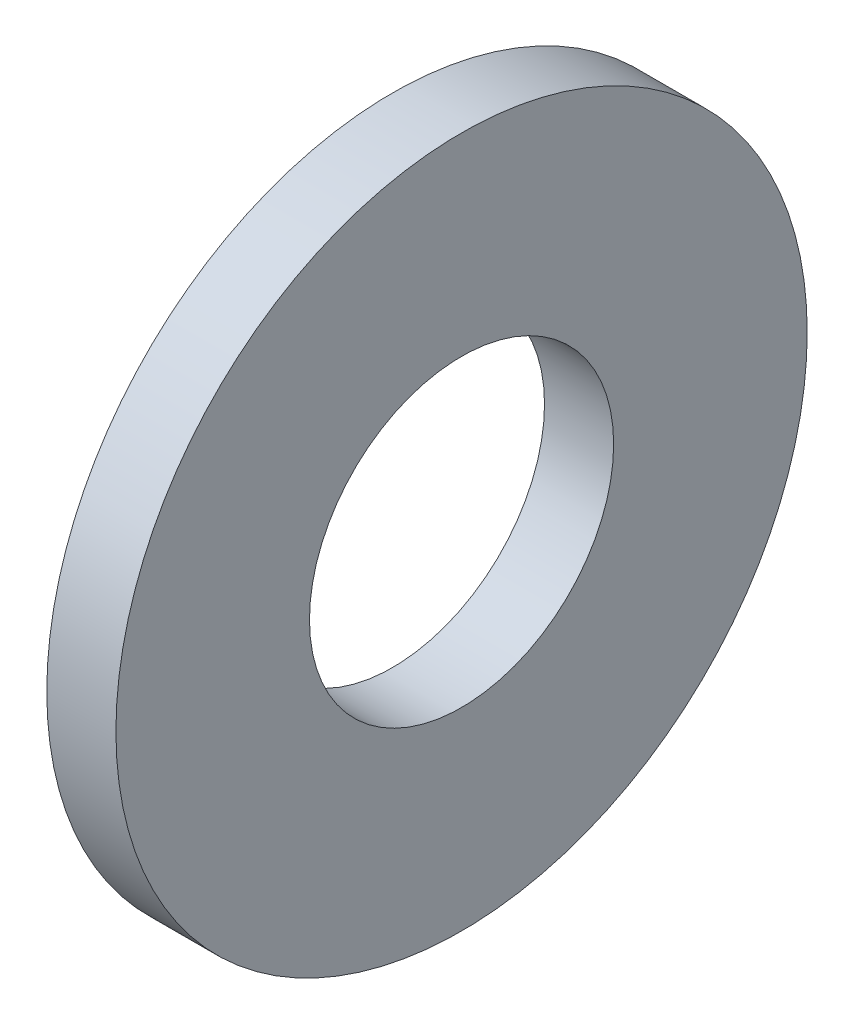
SolidWorks part; units mm, degrees
ref_plane "Plane1" through (0, 0, 0) normal (0, 0, 1) x (1, 0, 0)
ref_plane "Plane2" through (0, 0, 0) normal (0, 1, 0) x (1, 0, 0)
ref_plane "Plane3" through (0, 0, 0) normal (1, 0, 0) x (0, 0, -1)
sketch "Sketch1" plane through (0, 0, 0) normal (1, 0, 0) x (0, 0, -1)
  circle A0 centre (0, 0) radius 4.4
  circle A1 centre (0, 0) radius 10
  dimension "Insid_dia" = 8.8
  dimension "OutsideDia" = 20
extrude "Base-Extrude" add sketch "Sketch1" along normal blind 2
